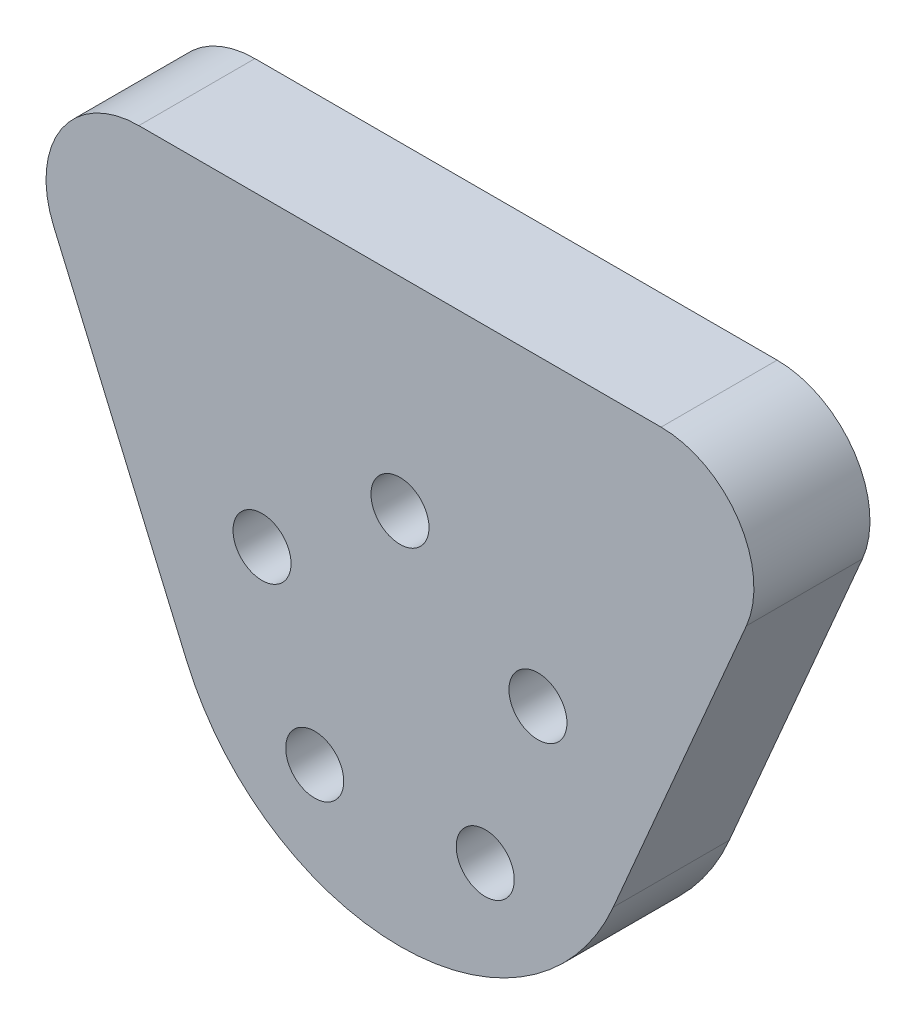
SolidWorks part; units mm, degrees
ref_plane "Alzado" through (0, 0, 0) normal (0, 0, 1) x (1, 0, 0)
ref_plane "Planta" through (0, 0, 0) normal (0, 1, 0) x (1, 0, 0)
ref_plane "Vista lateral" through (0, 0, 0) normal (1, 0, 0) x (0, 0, -1)
sketch "Croquis1" plane through (0, 0, 0) normal (0, 0, 1) x (1, 0, 0)
  line L0 (-45, 8) -> (0, 8)
  line L1 (-52.3516, -3.155) -> (-40.879, -29.8876)
  line L2 (7.3516, -3.155) -> (-4.121, -29.8876)
  line L3 (-22.5, 8) -> (-22.5, -22) construction
  arc A0 (7.3516, -3.155) -> (0, 8) centre (0, 0) ccw
  arc A1 (-45, 8) -> (-52.3516, -3.155) centre (-45, 0) ccw
  arc A2 (-40.879, -29.8876) -> (-4.121, -29.8876) centre (-22.5, -22) ccw
  circle A3 centre (-22.5, -22) radius 12.5 construction
  circle A4 centre (-22.5, -9.5) radius 2.5
  circle A5 centre (-10.6118, -18.1373) radius 2.5
  circle A6 centre (-15.1527, -32.1127) radius 2.5
  circle A7 centre (-29.8473, -32.1127) radius 2.5
  circle A8 centre (-34.3882, -18.1373) radius 2.5
  point P14 (-6.7347, -15.8223)
  point P15 (0, 0)
  point P16 (0, 0)
  point P25 (-22.5, -22)
  point P26 (0, 0)
  point P27 (0, 0)
  point P28 (-29.8473, -32.1127)
  point P29 (-15.1527, -32.1127)
  dimension "D1" = 20
  dimension "D2" = 8
  dimension "D5" = 25
  dimension "D6" = 5
  dimension "D3" = 45
  dimension "D4" = 30
  dimension "D7" = 5
extrude "Saliente-Extruir1" add sketch "Croquis1" along normal blind 10
